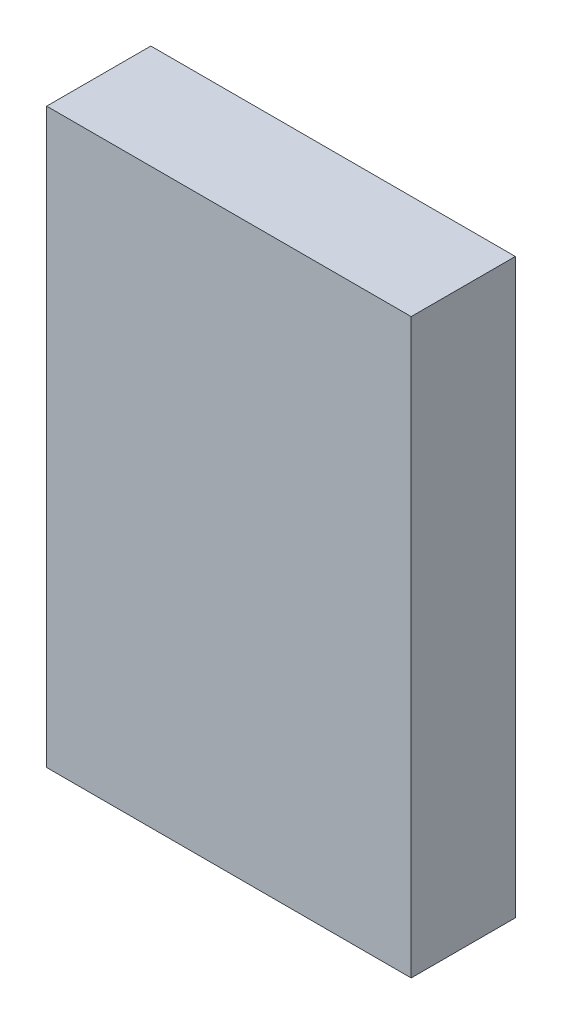
SolidWorks part; units mm, degrees
material "Oak"
ref_plane "Front Plane" through (0, 0, 0) normal (0, 0, 1) x (1, 0, 0)
ref_plane "Top Plane" through (0, 0, 0) normal (0, 1, 0) x (1, 0, 0)
ref_plane "Right Plane" through (0, 0, 0) normal (1, 0, 0) x (0, 0, -1)
sketch "Sketch1" plane through (0, 0, 0) normal (0, 0, 1) x (1, 0, 0)
  line L1 (-22.225, -34.925) -> (22.225, -34.925)
  line L2 (-22.225, -34.925) -> (-22.225, 34.925)
  line L3 (-22.225, 34.925) -> (22.225, 34.925)
  line L4 (22.225, -34.925) -> (22.225, 34.925)
  line L5 (-22.225, -34.925) -> (22.225, 34.925) construction
  line L6 (-22.225, 34.925) -> (22.225, -34.925) construction
  point P1 (0, 0)
  dimension "D1" = 69.85
  dimension "D2" = 44.45
extrude "Boss-Extrude1" add sketch "Sketch1" along normal mid plane 12.7
